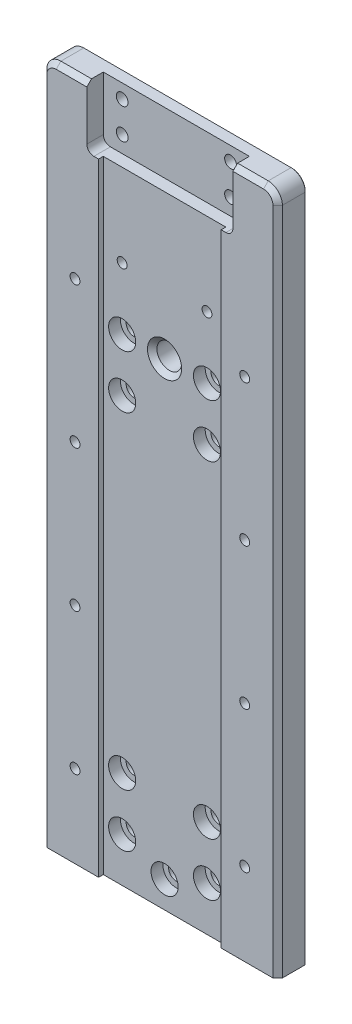
SolidWorks part; units mm, degrees
material "1060 Alloy"
ref_plane "Front Plane" through (0, 0, 0) normal (0, 0, 1) x (1, 0, 0)
ref_plane "Top Plane" through (0, 0, 0) normal (0, 1, 0) x (1, 0, 0)
ref_plane "Right Plane" through (0, 0, 0) normal (1, 0, 0) x (0, 0, -1)
sketch "Sketch1" plane through (0, 0, 0) normal (0, 0, 1) x (1, 0, 0)
  line L1 (50, -145) -> (-50, -145)
  line L2 (50, -145) -> (50, 145)
  line L3 (50, 145) -> (-50, 145)
  line L4 (-50, -145) -> (-50, 145)
  line L5 (50, -145) -> (-50, 145) construction
  line L6 (50, 145) -> (-50, -145) construction
  point P0 (0, 0)
  dimension "D1" = 100
  dimension "D2" = 290
extrude "Boss-Extrude1" add sketch "Sketch1" along normal mid plane 12
sketch "Sketch2" plane through (0, 0, 6) normal (0, 0, 1) x (1, 0, 0)
  line L0 (0, 132) -> (0, 0) construction
  line L1 (31, 119) -> (-31, 119)
  line L2 (31, 119) -> (31, 145)
  line L3 (31, 145) -> (-31, 145)
  line L4 (-31, 119) -> (-31, 145)
  line L5 (31, 119) -> (-31, 145) construction
  line L6 (31, 145) -> (-31, 119) construction
  line L7 (50, 145) -> (-50, 145) construction
  point P0 (0, 132)
  dimension "D1" = 62
  dimension "D2" = 26
extrude "Cut-Extrude1" cut sketch "Sketch2" against normal blind 7
sketch "Sketch3" plane through (0, 0, 6) normal (0, 0, 1) x (1, 0, 0)
  line L0 (-50, -145) -> (50, -145) construction
  line L1 (26, 145) -> (-26, 145)
  line L2 (26, 145) -> (26, -145)
  line L3 (26, -145) -> (-26, -145)
  line L4 (-26, 145) -> (-26, -145)
  line L5 (26, 145) -> (-26, -145) construction
  line L6 (26, -145) -> (-26, 145) construction
  point P0 (0, 0)
  dimension "D1" = 52
extrude "Cut-Extrude2" cut sketch "Sketch3" against normal blind 2
sketch "Sketch4" plane through (0, 0, -6) normal (0, 0, 1) x (1, 0, 0)
  line L0 (0, 132.5) -> (0, 0) construction
  line L1 (23, 126) -> (-23, 126) construction
  line L2 (23, 126) -> (23, 139) construction
  line L3 (23, 139) -> (-23, 139) construction
  line L4 (-23, 126) -> (-23, 139) construction
  line L5 (23, 126) -> (-23, 139) construction
  line L6 (23, 139) -> (-23, 126) construction
  line L7 (31, 145) -> (-31, 145) construction
  line L8 (-18, 83.89) -> (-18, 35.09) construction
  line L9 (-36, 145) -> (-36, -110) construction
  line L10 (-31, 145) -> (-50, 145) construction
  line L11 (-50, -145) -> (-26, -145) construction
  line L12 (0, 0) -> (0, -145) construction
  line L13 (-26, -145) -> (26, -145) construction
  line L14 (50, 23.09) -> (-50, 23.09) construction
  line L15 (18, -103.65) -> (-18, -103.65) construction
  line L16 (18, -103.65) -> (18, -126.15) construction
  line L17 (18, -126.15) -> (-18, -126.15) construction
  line L18 (-18, -103.65) -> (-18, -126.15) construction
  line L19 (18, -103.65) -> (-18, -126.15) construction
  line L20 (18, -126.15) -> (-18, -103.65) construction
  line L21 (50, 23.09) -> (50, 73.89) construction
  line L22 (50, 73.89) -> (-50, 73.89) construction
  line L23 (-50, 23.09) -> (-50, 73.89) construction
  line L24 (50, 23.09) -> (-50, 73.89) construction
  line L25 (50, 73.89) -> (-50, 23.09) construction
  circle A0 centre (-23, 139) radius 2.5
  circle A1 centre (23, 139) radius 2.5
  circle A2 centre (23, 126) radius 2.5
  circle A3 centre (-23, 126) radius 2.5
  circle A4 centre (0, 57.59) radius 5.25
  circle A5 centre (-18, 83.89) radius 2.1
  circle A6 centre (-18, 57.59) radius 3.3
  circle A7 centre (-18, 35.09) radius 3.3
  circle A9 centre (-36, 70) radius 2.1
  circle A10 centre (-36, 58.75) radius 2.1 construction
  circle A11 centre (-36, 10) radius 2.1
  circle A12 centre (-36, -110) radius 2.1
  circle A13 centre (-36, -50) radius 2.1
  circle A14 centre (-18, -103.65) radius 3.3
  circle A15 centre (-18, -126.15) radius 3.3
  circle A16 centre (18, -103.65) radius 3.3
  circle A17 centre (18, -126.15) radius 3.3
  circle A18 centre (0, -133.65) radius 3.3
  circle A20 centre (36, 70) radius 2.1
  circle A21 centre (36, 58.75) radius 2.1 construction
  circle A22 centre (18, 83.89) radius 2.1
  circle A23 centre (18, 35.09) radius 3.3
  circle A24 centre (18, 57.59) radius 3.3
  circle A25 centre (36, 10) radius 2.1
  circle A26 centre (36, -50) radius 2.1
  circle A27 centre (36, -110) radius 2.1
  point P0 (0, 132.5)
  point P36 (0, -114.9)
  point P68 (0, 48.49)
  dimension "D1" = 5
  dimension "D5" = 10.5
  dimension "D12" = 4.2
  dimension "D19" = 6.6
  dimension "D9" = 6.6
  dimension "D2" = 13
  dimension "D3" = 46
  dimension "D4" = 6
  dimension "D8" = 18
  dimension "D10" = 22.5
  dimension "D11" = 36
  dimension "D13" = 35
  dimension "D14" = 60
  dimension "D15" = 60
  dimension "D16" = 48.75
  dimension "D17" = 11.25
  dimension "D20" = 11.35
  dimension "D21" = 36
  dimension "D23" = 22.5
  dimension "D24" = 100
  dimension "D25" = 50.8
  dimension "D7" = 10
  dimension "D6" = 12
  dimension "D18" = 168.09
  dimension "D22" = 7.5
extrude "Cut-Extrude HOLES" cut sketch "Sketch4" along normal blind 21
fillet "Fillet1" radius 3 2 edges at (31, 119, 2.5) (-31, 119, 2.5)
fillet "Fillet2" radius 6 2 edges at (50, 145, 0) (-50, 145, 0)
chamfer "Chamfer1" distance 2 angle 45 6 edges at (50, -3, 6) (48.2426, 143.2426, 6) (37.5, 145, 6) (-50, -3, 6) (-48.2426, 143.2426, 6) (-37.5, 145, 6)
sketch "Sketch5" plane through (0, 0, 4) normal (0, 0, 1) x (1, 0, 0)
  circle A1 centre (-18, 57.59) radius 5.75
  circle A2 centre (-18, 35.09) radius 5.75
  circle A3 centre (18, 35.09) radius 5.75
  circle A4 centre (18, 57.59) radius 5.75
  circle A6 centre (18, -103.65) radius 5.75
  circle A7 centre (-18, -103.65) radius 5.75
  circle A8 centre (-18, -126.15) radius 5.75
  circle A9 centre (0, -133.65) radius 5.75
  circle A10 centre (18, -126.15) radius 5.75
  dimension "D1" = 11.5
extrude "Cut-Extrude5" cut sketch "Sketch5" against normal blind 5
chamfer "Chamfer2" distance 2 angle 45 1 edges at (-5.25, 57.59, 4)
chamfer "Chamfer3" distance 0.3 angle 45 5 edges at (-50, -3, -6) (-48.2426, 143.2426, -6) (0, 145, -6) (48.2426, 143.2426, -6) (50, -3, -6)
equation "\"M5_tap\"=4.2mm\t\t\t\t\t\t\t' Below you can do mesurements as follows: cm, mm, ft, in, m, "
equation "\"M5_clearence\"=5.5mm"
equation "\"M6_tap\"=5mm"
equation "\"M6_clearence\"=6.6mm"
equation "\"D1@Sketch4\"=\"M6_tap\""
equation "\"D12@Sketch4\"=\"M5_tap\""
equation "\"D19@Sketch4\"=\"M6_clearence\""
equation "\"work_area_width\"=1100mm"
equation "\"work_area_depth\"=900mm"
equation "\"steel_base_width\"=3in\t"
equation "\"steel_base_height\"=2in"
equation "\"steel_base_wall_thickness\"=0.125in"
equation "\"steel_base_radius\"=6mm"
equation "\"steel_sides_width\"=3in\t\t\t\t\t'this tube is rotated so flip width/height"
equation "\"steel_sides_height\"=2in\t\t\t\t'this tube is rotated so flip width/height"
equation "\"steel_sides_wall_thickness\"=0.125in"
equation "\"steel_sides_radius\"=6mm"
equation "\"steel_gantry_width\"=4in\t\t\t\t'this tube is rotated so flip width/height"
equation "\"steel_gantry_height\"=3in\t\t\t\t'this tube is rotated so flip width/height"
equation "\"steel_gantry_wall_thickness\"=0.125in"
equation "\"steel_gantry_radius\"=6mm"
equation "\"steel_rollers_width\"=3in"
equation "\"steel_rollers_height\"=2in\t\t\t\t'keep as low as possible as this increases how big plastic parts are"
equation "\"steel_rollers_wall_thickness\"=0.125in"
equation "\"steel_rollers_radius\"=6mm"
equation "\"steel_zbox_width\"=4in\t\t\t\t\t'if the gantry height (rotated) is too thick, a wider zbox is necessary"
equation "\"steel_zbox_height\"=2in\t\t\t\t\t'hole patteren changes as the zbox and gantry height (rotated) changes."
equation "\"steel_zbox_wall_thickness\"=0.125in"
equation "\"steel_zbox_radius\"=6mm"
equation "\"alu_zangle_width\"=3.5in\t\t\t\t\t'check that it doesn't interfer with the gantry"
equation "\"alu_zangle_height\"=2in"
equation "\"alu_zangle_wall_thickness\"=0.25in\t\t\t'check that it doesn't interfer with the gantry"
equation "\"D9@Sketch4\"=\"M6_clearence\""
equation "\"D25@Sketch4\"=\"steel_zbox_height\""
equation "\"D6@Sketch4\"=\"steel_zbox_radius\"*2"
equation "\"D18@Sketch4\"=\"steel_gantry_width\" + \"alu_zangle_wall_thickness\" + 60.14"
equation "\"D20@Sketch4\"=\"alu_zangle_wall_thickness\" + 5"
